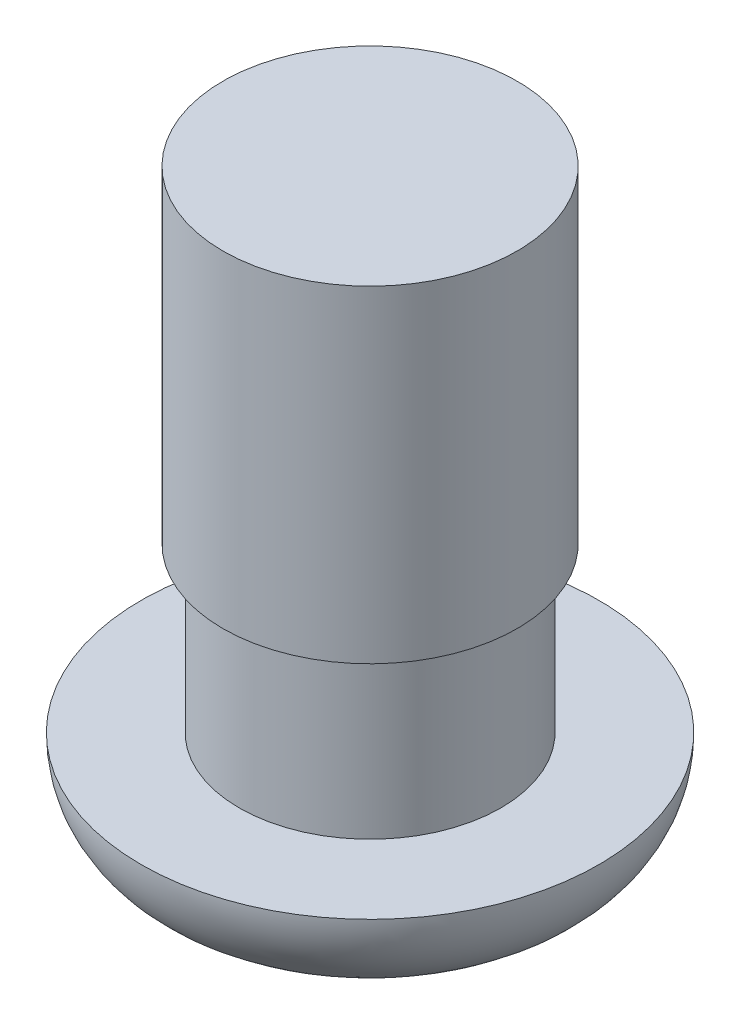
SolidWorks part; units mm, degrees
material "ASTM A36"
ref_plane "Plano frontal" through (0, 0, 0) normal (0, 0, 1) x (1, 0, 0)
ref_plane "Plano superior" through (0, 0, 0) normal (0, 1, 0) x (1, 0, 0)
ref_plane "Plano direito" through (0, 0, 0) normal (1, 0, 0) x (0, 0, -1)
sketch "Esboço1" plane through (0, 0, 0) normal (1, 0, 0) x (0, 0, -1)
  line L0 (0, 0) -> (-2, 0)
  line L1 (-3.5, 1.5) -> (-2, 1.5)
  line L2 (-2, 1.5) -> (-2, 4)
  line L3 (-2, 4) -> (-2.25, 4)
  line L4 (-2.25, 4) -> (-2.25, 9)
  line L5 (-2.25, 9) -> (0, 9)
  line L6 (0, 9) -> (0, 0)
  line L7 (0, 0) -> (0, -12633.3702) construction
  arc A0 (-2, 0) -> (-3.5, 1.5) centre (-2, 1.5) cw
  dimension "D1" = 9
  dimension "D2" = 7
  dimension "D3" = 1.5
  dimension "D4" = 2.5
  dimension "D5" = 4
  dimension "D6" = 4.5
revolve "Revolução1" add sketch "Esboço1" angle 360 about L7
